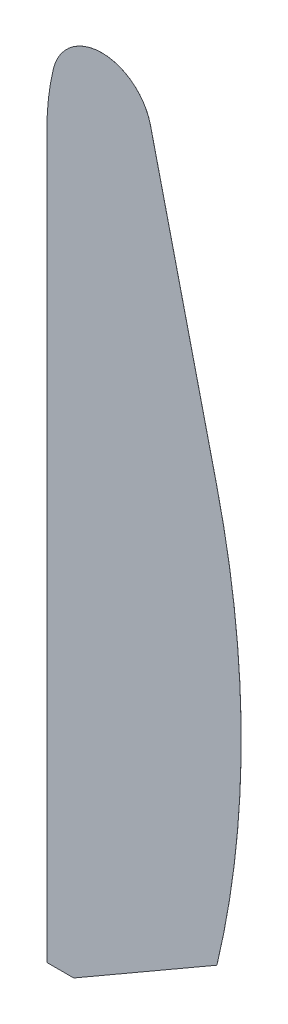
SolidWorks part; units mm, degrees
ref_plane "Front Plane" through (0, 0, 0) normal (1, 0, 0) x (0, 1, 0)
ref_plane "Top Plane" through (0, 0, 0) normal (0, 0, 1) x (0, 1, 0)
ref_plane "Right Plane" through (0, 0, 0) normal (0, 1, 0) x (-1, 0, 0)
sketch "Sketch1" plane through (0, 0, 0) normal (0, 0, 1) x (0, 1, 0)
  line L0 (0, 0) -> (0, 50000) construction
  line L1 (0, 0) -> (50000, 0) construction
  line L2 (143.5634, 601.065) -> (1381.2364, 932.6984) construction
  line L3 (0, 0) -> (134.85, 0)
  line L4 (0, 0) -> (0, -5)
  line L5 (0, -5) -> (15.4261, -31.7187)
  line L6 (145, -19.3141) -> (92.7835, -31.7187)
  line L7 (0, 0) -> (54.1048, -36.25)
  line L8 (0, 0) -> (145, -19.3141)
  arc A0 (134.85, 0) -> (145, -1.1891) centre (134.85, -43.9147) cw
  arc A1 (145, -1.1891) -> (145, -19.3141) centre (142.8471, -10.2516) cw
  arc A2 (15.4261, -31.7187) -> (92.7835, -31.7187) centre (54.1048, 131.0963) ccw
  dimension "D1" = 5
  dimension "D2" = 31.7187
  dimension "D3" = 134.85
  dimension "Span" = 145
  dimension "Chord" = 36.25
  dimension "D4" = 30
  dimension "D5" = 18.125
extrude "Boss-Extrude1" add sketch "Sketch1" along normal blind 0.01 contours L6 A2 L5 L4 L3 A0 A1
equation "\"D3@Sketch1\"=\"Span@Sketch1\"*0.93"
equation "\"D2@Sketch1\"=\"Chord@Sketch1\"*0.875"
equation "\"Chord@Sketch1\"=\"Span@Sketch1\"/4"
equation "\"D5@Sketch1\"=\"Chord@Sketch1\"/2"
